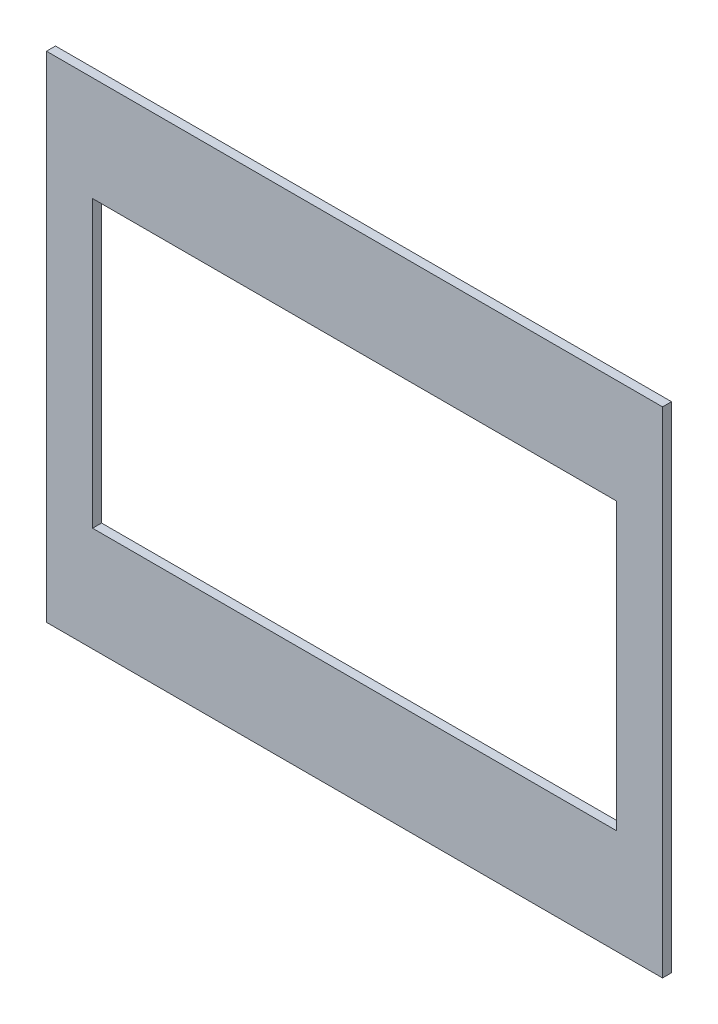
SolidWorks part; units mm, degrees
ref_plane "Front Plane" through (0, 0, 0) normal (0, 0, 1) x (1, 0, 0)
ref_plane "Top Plane" through (0, 0, 0) normal (0, 1, 0) x (1, 0, 0)
ref_plane "Right Plane" through (0, 0, 0) normal (1, 0, 0) x (0, 0, -1)
sketch "Sketch1" plane through (0, 0, 0) normal (0, 0, 1) x (1, 0, 0)
  line L1 (-58.25, -31.75) -> (58.25, -31.75)
  line L2 (-58.25, -31.75) -> (-58.25, 31.75)
  line L3 (-58.25, 31.75) -> (58.25, 31.75)
  line L4 (58.25, -31.75) -> (58.25, 31.75)
  line L5 (-58.25, -31.75) -> (58.25, 31.75) construction
  line L6 (-58.25, 31.75) -> (58.25, -31.75) construction
  line L7 (-68.5, -55) -> (68.5, -55)
  line L8 (-68.5, -55) -> (-68.5, 55)
  line L9 (-68.5, 55) -> (68.5, 55)
  line L10 (68.5, -55) -> (68.5, 55)
  line L11 (-68.5, -55) -> (68.5, 55) construction
  line L12 (-68.5, 55) -> (68.5, -55) construction
  point P0 (0, 0)
  point P6 (0, 0)
  dimension "D1" = 116.5
  dimension "D2" = 63.5
  dimension "D3" = 110
  dimension "D4" = 137
extrude "Boss-Extrude1" add sketch "Sketch1" along normal blind 2
